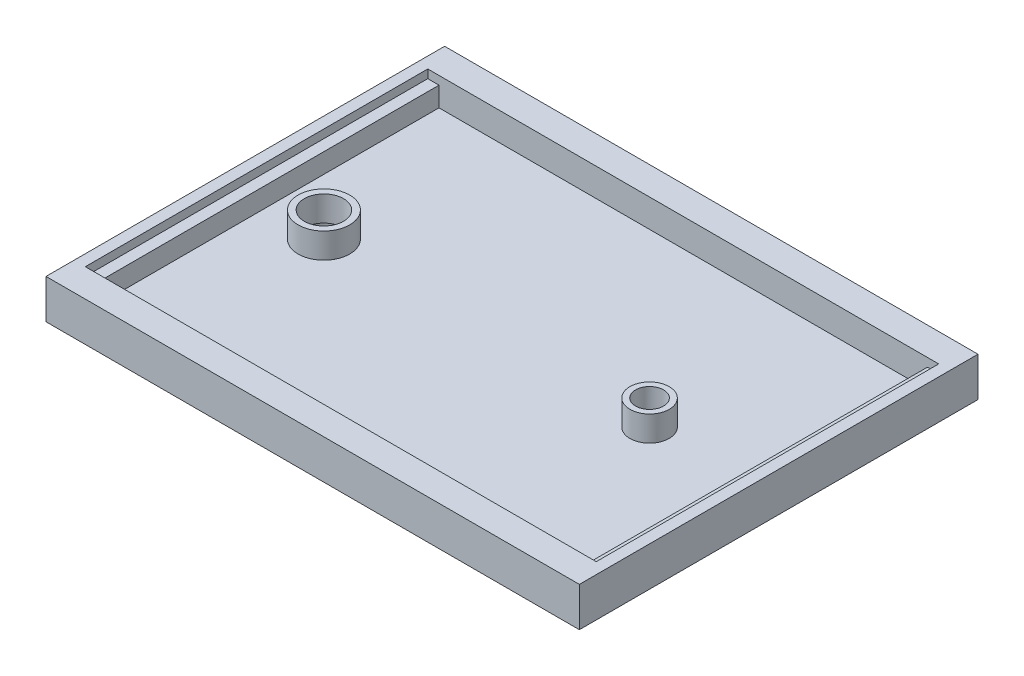
SolidWorks part; units mm, degrees
ref_plane "Front Plane" through (0, 0, 0) normal (0, 0, 1) x (1, 0, 0)
ref_plane "Top Plane" through (0, 0, 0) normal (0, 1, 0) x (1, 0, 0)
ref_plane "Right Plane" through (0, 0, 0) normal (1, 0, 0) x (0, 0, -1)
sketch "Master_Geometry" plane through (0, 0, 0) normal (0, 0, 1) x (1, 0, 0)
  line L0 (0, 6.611) -> (0, -8.3361) construction
  line L1 (-45, -1) -> (45, -1) construction
  line L2 (-45, -1) -> (-45, 1) construction
  line L3 (-45, 1) -> (45, 1) construction
  line L4 (45, -1) -> (45, 1) construction
  line L5 (-45, -1) -> (45, 1) construction
  line L6 (-45, 1) -> (45, -1) construction
  line L7 (-47.5, -5) -> (-47.5, 0)
  line L8 (-47.5, -7) -> (47.5, -7)
  line L9 (-47.5, -7) -> (-47.5, -5)
  line L10 (-43.5, -5) -> (43.5, -5)
  line L11 (47.5, -7) -> (47.5, -5)
  line L12 (43.5, -1.5) -> (43.5, -5)
  line L13 (45.5, -1.5) -> (43.5, -1.5)
  line L14 (-47.5, 0) -> (-45.5, 0)
  line L15 (-45.5, 0) -> (-45.5, -1.5)
  line L16 (-45.5, -1.5) -> (-43.5, -1.5)
  line L17 (-43.5, -1.5) -> (-43.5, -5)
  line L18 (45.5, 0) -> (45.5, -1.5)
  line L19 (47.5, 0) -> (45.5, 0)
  line L20 (47.5, -5) -> (47.5, 0)
  point P0 (0, 0)
  point P7 (0, -6)
  dimension "D1" = 90
  dimension "D2" = 2
  dimension "D3" = 4
  dimension "D4" = 2
  dimension "D6" = 7
  dimension "D7" = 3.5
  dimension "D8" = 2
  dimension "D9" = 2
  dimension "D5" = 0.5
extrude "PCB_Stand" add sketch "Master_Geometry" along normal mid plane 61
ref_plane "PCB_Midplane_A" through (0, 0, 0) normal (1, 0, 0) x (0, 0, -1)
ref_plane "PCB_Midplane_B" through (0, 0, 0) normal (0, 0, 1) x (1, 0, 0)
sketch "Sketch3" plane through (0, 0, 30.5) normal (0, 0, 1) x (1, 0, 0)
  line L0 (-47.5, 0) -> (-47.5, -7)
  line L1 (-47.5, -7) -> (47.5, -7)
  line L2 (47.5, -7) -> (47.5, 0)
  line L3 (47.5, 0) -> (-47.5, 0)
extrude "Extra_Bottom" add sketch "Sketch3" along normal blind 5
mirror "Mirror2" about plane through (0, 0, 0) normal (0, 0, 1) of "Extra_Bottom"
sketch "Sensor-Holes" plane through (0, -7, 0) normal (0, -1, 0) x (1, 0, 0)
  line L0 (-47.5, 35.5) -> (-47.5, -35.5) construction
  line L3 (55, 0) -> (-55, 0) construction
  circle A0 centre (-33.5, 0) radius 4.6
  circle A1 centre (24.5, 0) radius 2.5
  point P4 (0, 0)
  point P9 (0, 0)
  dimension "D4" = 9.2
  dimension "D5" = 5
  dimension "D1" = 58
  dimension "D2" = 14
extrude "Sensor_Holes" cut sketch "Sensor-Holes" against normal through all
sketch "Sketch4" plane through (0, -5, 0) normal (0, 1, 0) x (1, 0, 0)
  circle A0 centre (24.5, 0) radius 3.5
  circle A1 centre (-33.5, 0) radius 3.5
  circle A2 centre (24.5, 0) radius 2.5 construction
  circle A3 centre (-33.5, 0) radius 4.6 construction
  circle A4 centre (24.5, 0) radius 2.5
  circle A5 centre (-33.5, 0) radius 4.6
  dimension "D1" = 7
  dimension "D2" = 7
extrude "Cylinder" add sketch "Sketch4" along normal blind 4.5
equation "\"pcb_length\"= 90mm"
equation "\"pcb_width\"= 60mm"
equation "\"pcb_depth\"= 2mm"
equation "\"rel_tol\"= 0.5mm"
equation "\"dist_pcb_bottom\"= 4mm"
equation "\"thickness_bottom\"= 2mm"
equation "\"dist_pcb_edge\" = 2mm"
equation "\"stair_length\"= 2mm"
equation "\"stair_height\"= \"dist_pcb_bottom\" - \"rel_tol\""
equation "\"D1@Master_Geometry\" = \"pcb_length\""
equation "\"D2@Master_Geometry\" = \"pcb_depth\""
equation "\"D3@Master_Geometry\" = \"dist_pcb_bottom\""
equation "\"D4@Master_Geometry\" = \"thickness_bottom\""
equation "\"height_bottom\"= 7mm"
equation "\"D6@Master_Geometry\" = \"height_bottom\""
equation "\"D7@Master_Geometry\" = \"stair_height\""
equation "\"D8@Master_Geometry\" = \"stair_length\""
equation "\"D9@Master_Geometry\" = \"dist_pcb_edge\""
equation "\"D5@Master_Geometry\" = \"rel_tol\""
equation "\"pcb_extra\"= 8mm"
equation "\"dist_ir_tof\"= 58mm"
equation "\"dist_tof_edge\"= 48mm"
equation "\"D1@Sensor-Holes\" = \"dist_ir_tof\""
equation "\"diameter_ir\"= 9.2mm"
equation "\"diameter_tof\"= 5mm"
equation "\"D5@Sensor-Holes\"=\"diameter_tof\""
equation "\"D4@Sensor-Holes\"=\"diameter_ir\""
equation "\"D1@Sketch4\"=\"diameter_tof\"+2mm"
equation "\"D1@Cylinder\" = 5mm - \"rel_tol\""
equation "\"D2@Sketch4\"=\"diameter_tof\"+2mm"
